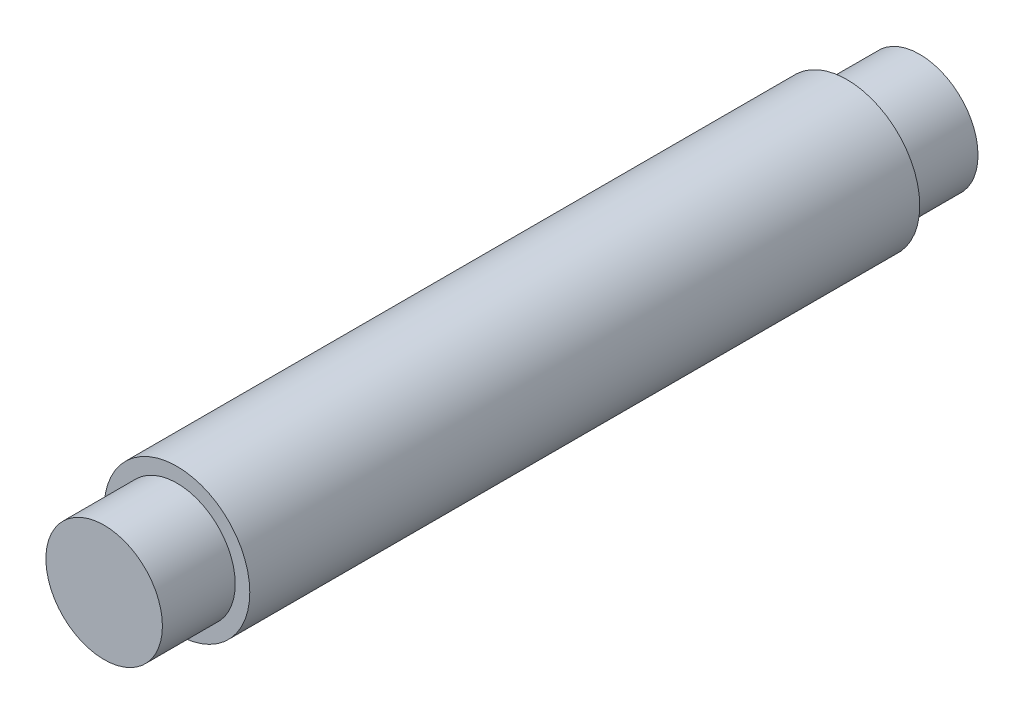
SolidWorks part; units mm, degrees
ref_plane "Front Plane" through (0, 0, 0) normal (0, 0, 1) x (1, 0, 0)
ref_plane "Top Plane" through (0, 0, 0) normal (0, 1, 0) x (1, 0, 0)
ref_plane "Right Plane" through (0, 0, 0) normal (1, 0, 0) x (0, 0, -1)
sketch "Sketch1" plane through (0, 0, 0) normal (0, 0, 1) x (1, 0, 0)
  circle A0 centre (0, 0) radius 2.5
extrude "Boss-Extrude1" add sketch "Sketch1" along normal blind 23
sketch "Sketch2" plane through (0, 0, 23) normal (0, 0, 1) x (1, 0, 0)
  circle A0 centre (0, 0) radius 2
extrude "Boss-Extrude2" add sketch "Sketch2" along normal blind 2.5
sketch "Sketch3" plane through (0, 0, 0) normal (0, 0, -1) x (-1, 0, 0)
  circle A0 centre (0, 0) radius 2
extrude "Boss-Extrude3" add sketch "Sketch3" along normal blind 2.5
